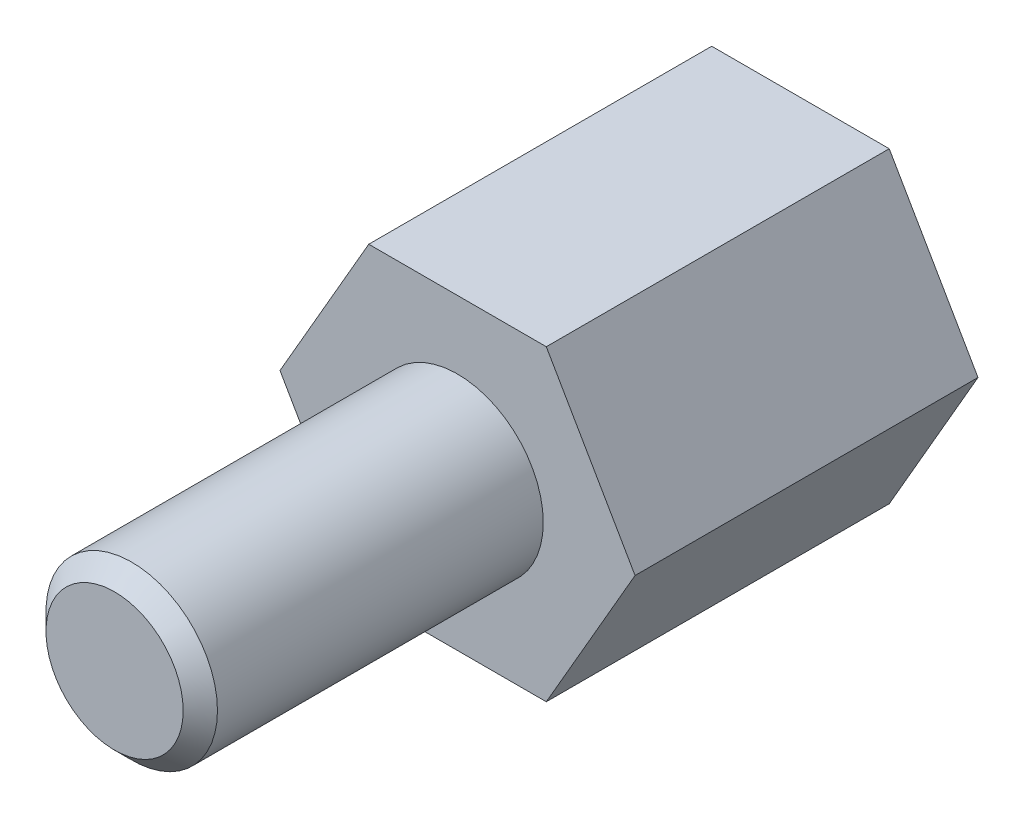
SolidWorks part; units mm, degrees
ref_plane "前视基准面" through (0, 0, 0) normal (0, 0, 1) x (1, 0, 0)
ref_plane "上视基准面" through (0, 0, 0) normal (0, 1, 0) x (1, 0, 0)
ref_plane "右视基准面" through (0, 0, 0) normal (1, 0, 0) x (0, 0, -1)
sketch "草图1" plane through (0, 0, 0) normal (0, 0, 1) x (1, 0, 0)
  line L1 (-1.5531, 2.69) -> (-3.1061, 0)
  line L2 (-3.1061, 0) -> (-1.5531, -2.69)
  line L3 (-1.5531, -2.69) -> (1.5531, -2.69)
  line L4 (1.5531, -2.69) -> (3.1061, 0)
  line L5 (3.1061, 0) -> (1.5531, 2.69)
  line L6 (1.5531, 2.69) -> (-1.5531, 2.69)
  circle A0 centre (0, 0) radius 2.69 construction
  dimension "D1" = 5.38
extrude "凸台-拉伸1" add sketch "草图1" along normal blind 6
sketch "草图2" plane through (0, 0, 6) normal (0, 0, 1) x (1, 0, 0)
  circle A0 centre (0, 0) radius 1.5
  dimension "D1" = 3
extrude "凸台-拉伸2" add sketch "草图2" along normal blind 6
hole_wizard "M3 螺纹孔1" positions "草图4" profile "草图3" tap size "M3" standard "GB"
sketch "草图4" plane through (0, 0, 0) normal (0, 0, -1) x (-1, 0, 0)
  point P0 (0, 0)
sketch "草图3" plane through (0, 0, 0) normal (1, 0, 0) x (0, 1, 0)
  line L0 (0, 0) -> (0, 5.7511)
  line L1 (0, 5.7511) -> (1.25, 5)
  line L2 (1.25, 5) -> (1.25, 0)
  line L5 (1.25, 0) -> (0, 0)
  line L10 (0, 5.7511) -> (-1.25, 5) construction
  line L11 (0, -6.35) -> (0, 107.95) construction
  dimension "螺纹孔钻头直径" = 2.5
  dimension "螺纹孔钻头深度" = 5
  dimension "导头角度" = 118
cosmetic thread "孔螺蚊线1" parameters "D1"=4.5, "D2"=3
chamfer "倒角1" distance 0.3 angle 45 1 edges at (1.5, 0, 12)
